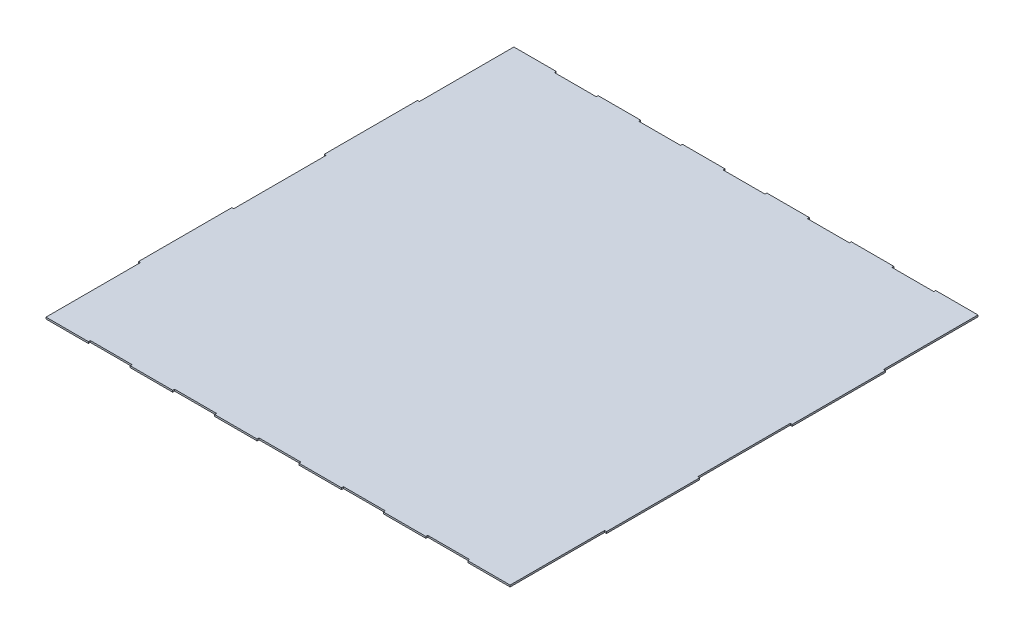
SolidWorks part; units mm, degrees
ref_plane "Front Plane" through (0, 0, 0) normal (0, 0, 1) x (1, 0, 0)
ref_plane "Top Plane" through (0, 0, 0) normal (0, 1, 0) x (1, 0, 0)
ref_plane "Right Plane" through (0, 0, 0) normal (1, 0, 0) x (0, 0, -1)
sketch "oneSide" plane through (0, 0, 0) normal (0, 1, 0) x (1, 0, 0)
  line L0 (-216.6667, 216.6667) -> (-216.6667, 218.4267)
  line L1 (-177.1127, 216.6667) -> (-138.0388, 216.6667)
  line L2 (-218.4267, 130.16) -> (-218.4267, 43.1733)
  line L4 (216.6667, 216.6667) -> (216.6667, 130.16)
  line L5 (-216.6667, 218.4267) -> (-177.1127, 218.4267)
  line L6 (-177.1127, 218.4267) -> (-177.1127, 216.6667)
  line L7 (-98.3248, 216.6667) -> (-59.2509, 216.6667)
  line L8 (-138.0388, 218.4267) -> (-98.3248, 218.4267)
  line L9 (-138.0388, 218.4267) -> (-138.0388, 216.6667)
  line L10 (-19.537, 216.6667) -> (19.537, 216.6667)
  line L11 (-98.3248, 218.4267) -> (-98.3248, 216.6667)
  line L12 (-59.2509, 218.4267) -> (-19.537, 218.4267)
  line L13 (-59.2509, 218.4267) -> (-59.2509, 216.6667)
  line L14 (59.2509, 216.6667) -> (98.3248, 216.6667)
  line L15 (-19.537, 218.4267) -> (-19.537, 216.6667)
  line L16 (19.537, 218.4267) -> (59.2509, 218.4267)
  line L17 (19.537, 218.4267) -> (19.537, 216.6667)
  line L18 (138.0388, 216.6667) -> (177.1127, 216.6667)
  line L19 (59.2509, 218.4267) -> (59.2509, 216.6667)
  line L20 (98.3248, 218.4267) -> (138.0388, 218.4267)
  line L21 (98.3248, 218.4267) -> (98.3248, 216.6667)
  line L22 (216.6667, 0) -> (-216.6667, 0)
  line L23 (138.0388, 218.4267) -> (138.0388, 216.6667)
  line L24 (177.1127, 218.4267) -> (216.6667, 218.4267)
  line L25 (177.1127, 218.4267) -> (177.1127, 216.6667)
  line L26 (216.6667, 43.1733) -> (216.6667, 0)
  line L27 (216.6667, 218.4267) -> (216.6667, 216.6667)
  line L28 (218.4267, 130.16) -> (216.6667, 130.16)
  line L29 (-218.4267, 130.16) -> (-216.6667, 130.16)
  line L30 (-216.6667, 216.6667) -> (-216.6667, 130.16)
  line L31 (-218.4267, 43.1733) -> (-216.6667, 43.1733)
  line L32 (218.4267, 130.16) -> (218.4267, 43.1733)
  line L33 (218.4267, 43.1733) -> (216.6667, 43.1733)
  line L34 (-216.6667, 43.1733) -> (-216.6667, 0)
  point P5 (0, 0)
  dimension "D1" = 433.3333
  dimension "D3" = 1.76
  dimension "D2" = 216.6667
  dimension "D4" = 86.5067
  dimension "D6" = 39.0739
  dimension "D7" = 39.7139
  dimension "D8" = 39.5539
  dimension "D9" = 86.9867
extrude "Boss-Extrude1" add sketch "oneSide" along normal blind 1.6
mirror "Mirror1" about plane through (216.6667, 1.6, 0) normal (0, 0, -1) of "Boss-Extrude1"
equation "\"thinkness\"= \"epaisseur\""
equation "\"D3@oneSide\" = \"thinkness\" + \"jeu\""
equation "\"D1@Boss-Extrude1\"= \"thinkness\""
equation "\"D4@oneSide\"= \"largeur\" / 5 - \"jeu\""
equation "\"largeur\"= \"longueur\""
equation "\"D2@oneSide\"= \"largeur\" / 2mm"
equation "\"hauteur\"= 47.5"
equation "\"longueur\"= \"nbCarre\" * \"Coté\""
equation "\"D1@oneSide\"= \"longueur\""
equation "\"D6@oneSide\" = \"longueur\" / 11 - 2 * \"jeu\""
equation "\"jeu\"= 0.16"
equation "\"D7@oneSide\" = \"longueur\" / 11 + 2 * \"jeu\""
equation "\"D8@oneSide\"= \"longueur\" / 11 + \"jeu\""
equation "\"D9@oneSide\"= \"largeur\" / 5 + \"jeu\" * 2"
equation "\"Coté\"= 33.333333"
equation "\"nbCarre\"= 13"
equation "\"epaisseur\"= 1.6"
equation "\"rapportEncoche\"= 0.5"
